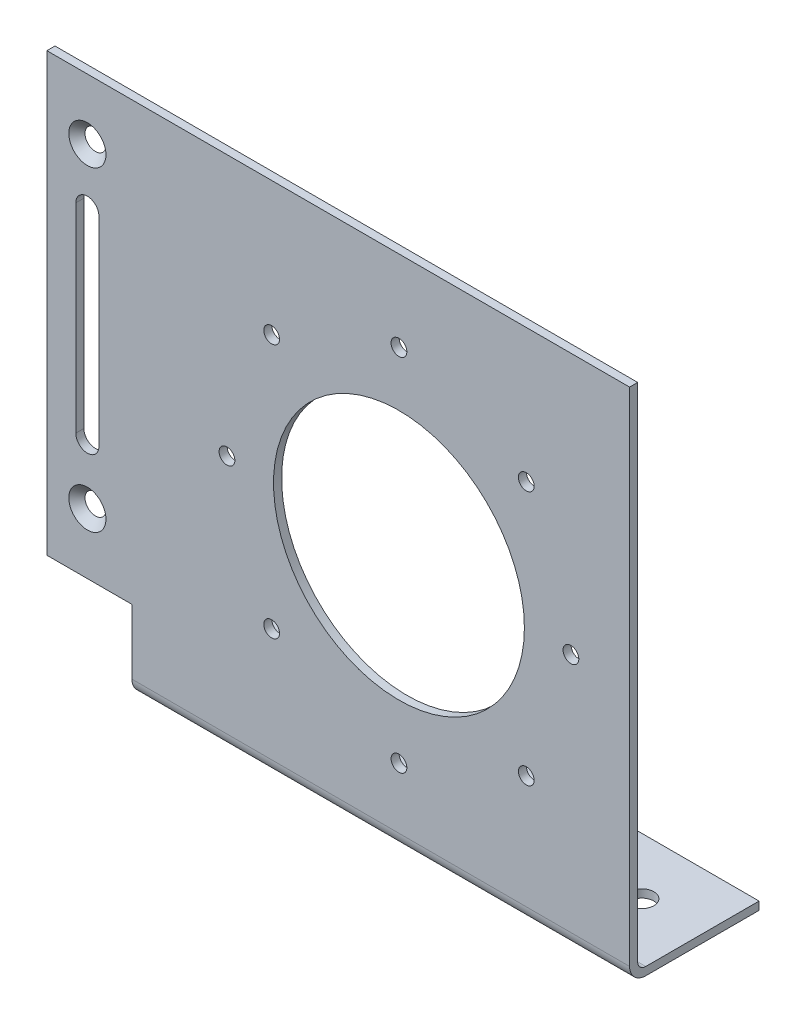
SolidWorks part; units mm, degrees
ref_plane "Ebene vorne" through (0, 0, 0) normal (0, 0, 1) x (1, 0, 0)
ref_plane "Ebene oben" through (0, 0, 0) normal (0, 1, 0) x (1, 0, 0)
ref_plane "Ebene rechts" through (0, 0, 0) normal (1, 0, 0) x (0, 0, -1)
sketch "Skizze1" plane through (0, 0, 0) normal (0, 0, 1) x (1, 0, 0)
  line L0 (-69.0234, -46.6458) -> (-48.0234, -46.6458)
  line L1 (74.9766, -66.6458) -> (-48.0234, -66.6458)
  line L2 (74.9766, -66.6458) -> (74.9766, 61.3542)
  line L3 (74.9766, 61.3542) -> (-69.0234, 61.3542)
  line L4 (-69.0234, -46.6458) -> (-69.0234, 61.3542)
  line L5 (74.9766, -66.6458) -> (-69.0234, 61.3542) construction
  line L6 (74.9766, 61.3542) -> (-48.0234, -39.2981) construction
  line L7 (-48.0234, -46.6458) -> (-48.0234, -66.6458)
  point P0 (0, 0)
  dimension "D1" = 128
  dimension "D2" = 144
  dimension "D3" = 21
  dimension "D4" = 20
extrude "Aufsatz-Linear austragen1" add sketch "Skizze1" along normal blind 2
sketch "Skizze2" plane through (0, 0, 0) normal (0, 0, -1) x (-1, 0, 0)
  line L1 (-74.9766, -66.6458) -> (48.0234, -66.6458)
  line L2 (-74.9766, -66.6458) -> (-74.9766, -64.6458)
  line L3 (-74.9766, -64.6458) -> (48.0234, -64.6458)
  line L5 (48.0234, -64.6458) -> (48.0234, -66.6458)
  line L6 (48.0234, -46.6458) -> (48.0234, -66.6458) construction
  dimension "D1" = 2
extrude "Aufsatz-Linear austragen2" add sketch "Skizze2" along normal blind 30
fillet "Verrundung1" radius 2 1 edges at (13.4766, -64.6458, 0)
fillet "Verrundung2" radius 4 1 edges at (13.4766, -66.6458, 2)
sketch "Skizze3" plane through (0, -66.6458, 0) normal (0, -1, 0) x (1, 0, 0)
  line L0 (-48.0234, -16) -> (74.9766, -16) construction
  line L1 (-48.0234, -2) -> (-48.0234, -30) construction
  line L2 (74.9766, -2) -> (74.9766, -30) construction
  circle A0 centre (-33.0234, -16) radius 3
  circle A1 centre (59.9766, -16) radius 3
  dimension "D1" = 15
  dimension "D3" = 6
  dimension "D2" = 15
extrude "Schnitt-Linear austragen1" cut sketch "Skizze3" against normal through all
hole_wizard "Formsenkung für M4 Senkschraube mit Innensechskant1" positions "Skizze6" profile "Skizze5" countersink size "M4" standard "DIN"
sketch "Skizze6" plane through (0, 0, 2) normal (0, 0, 1) x (1, 0, 0)
  line L0 (-59.0234, 61.3542) -> (-59.0234, -46.6458) construction
  line L1 (74.9766, 61.3542) -> (-69.0234, 61.3542) construction
  line L2 (-69.0234, -46.6458) -> (-48.0234, -46.6458) construction
  line L4 (-69.0234, 61.3542) -> (-69.0234, -46.6458) construction
  point P8 (-59.0234, 46.3542)
  point P10 (-59.0234, -31.6458)
  dimension "D1" = 15
  dimension "D2" = 15
  dimension "D3" = 10
sketch "Skizze5" plane through (-59.0234, -31.6458, 2) normal (1, 0, 0) x (0, -1, 0)
  line L0 (0, 0) -> (0, 13.2919)
  line L1 (0, 13.2919) -> (2.25, 11.94)
  line L2 (2.25, 11.94) -> (2.25, 2.34)
  line L3 (2.25, 2.34) -> (4.59, 0)
  line L5 (4.59, 0) -> (0, 0)
  line L6 (-2.25, 2.34) -> (-4.59, 0) construction
  line L10 (0, 13.2919) -> (-2.25, 11.94) construction
  line L11 (0, -6.35) -> (0, 107.95) construction
  dimension "Bohrerdurchmesser" = 4.5
  dimension "Bohrungstiefe" = 11.94
  dimension "Senkdurchmesser (Oben)" = 9.18
  dimension "Senkwinkel (Oben)" = 90
  dimension "Spitzenwinkel" = 118
sketch "Skizze7" plane through (0, 0, 2) normal (0, 0, 1) x (1, 0, 0)
  line L0 (-59.0234, 46.3542) -> (-59.0234, -31.6458) construction
  line L1 (-59.0234, -16.9352) -> (-59.0234, 32.3542) construction
  line L2 (-61.8817, -16.9352) -> (-61.8817, 32.3542)
  line L3 (-56.1652, -16.9352) -> (-56.1652, 32.3542)
  line L4 (74.9766, -62.6458) -> (74.9766, 61.3542) construction
  line L5 (74.9766, 61.3542) -> (-69.0234, 61.3542) construction
  circle A0 centre (17.9766, -3.1458) radius 44.5 construction
  circle A1 centre (17.9766, 41.3542) radius 1.95
  circle A2 centre (17.9766, -3.1458) radius 44.5 construction
  circle A3 centre (49.4428, 28.3204) radius 1.95
  circle A4 centre (17.9766, -3.1458) radius 44.5 construction
  circle A6 centre (17.9766, -3.1458) radius 44.5 construction
  circle A7 centre (49.4428, -34.6121) radius 1.95
  circle A8 centre (17.9766, -3.1458) radius 44.5 construction
  circle A9 centre (17.9766, -47.6458) radius 1.95
  circle A10 centre (17.9766, -3.1458) radius 44.5 construction
  circle A11 centre (-13.4897, -34.6121) radius 1.95
  circle A12 centre (17.9766, -3.1458) radius 44.5 construction
  circle A14 centre (17.9766, -3.1458) radius 44.5 construction
  circle A15 centre (-13.4897, 28.3204) radius 1.95
  circle A16 centre (17.9766, -3.1458) radius 31
  circle A17 centre (-26.5234, -3.1458) radius 1.95 [skipped]
  circle A18 centre (62.4766, -3.1458) radius 1.95 [skipped]
  circle A19 centre (17.9766, -3.1458) radius 42.5 construction
  circle A20 centre (-24.5234, -3.1458) radius 1.95
  circle A21 centre (60.4766, -3.1458) radius 1.95
  circle A22 centre (-59.0234, -31.6458) radius 2.59 construction
  circle A23 centre (-59.0234, 46.3542) radius 2.59 construction
  circle A24 centre (-59.0234, -31.6458) radius 2.59 construction
  circle A25 centre (-59.0234, 46.3542) radius 2.59 construction
  arc A26 (-61.8817, -16.9352) -> (-56.1652, -16.9352) centre (-59.0234, -16.9352) ccw
  arc A27 (-56.1652, 32.3542) -> (-61.8817, 32.3542) centre (-59.0234, 32.3542) ccw
  point P29 (17.9766, -3.1458)
  point P44 (-59.0234, 7.7095)
  dimension "D1" = 89
  dimension "D2" = 3.9
  dimension "D4" = 85
  dimension "D5" = 62
  dimension "D6" = 57
  dimension "D7" = 64.5
  dimension "D9" = 14
  dimension "D10" = 14.7106
  dimension "D3" = 8
extrude "Schnitt-Linear austragen2" cut sketch "Skizze7" against normal through all
